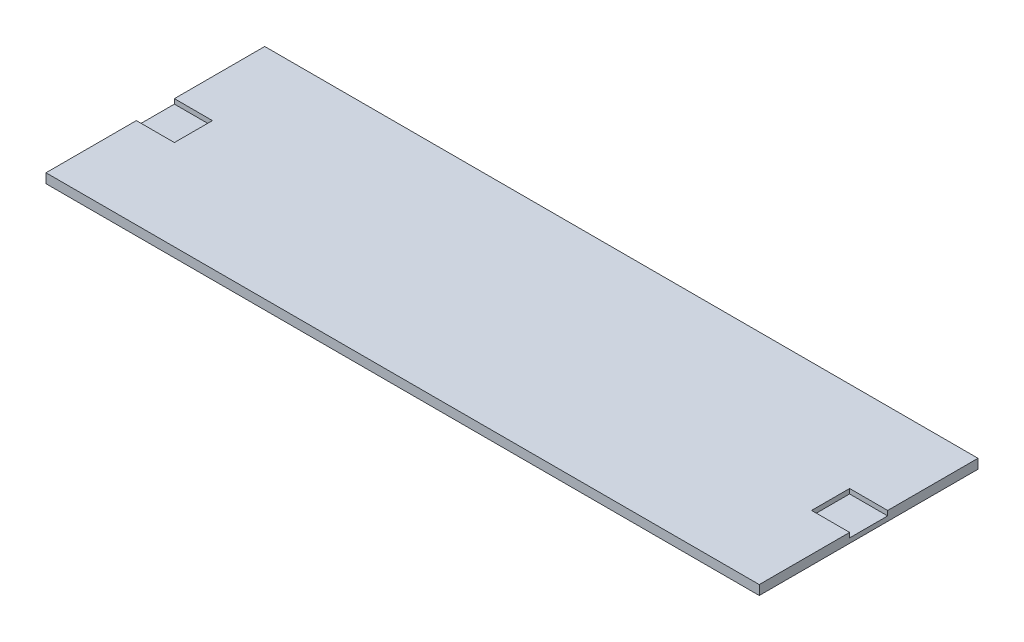
SolidWorks part; units mm, degrees
material "A-Glass Fiber"
ref_plane "Front Plane" through (0, 0, 0) normal (0, 0, 1) x (1, 0, 0)
ref_plane "Top Plane" through (0, 0, 0) normal (0, 1, 0) x (1, 0, 0)
ref_plane "Right Plane" through (0, 0, 0) normal (1, 0, 0) x (0, 0, -1)
sketch "Sketch1" plane through (0, 0, 0) normal (0, 1, 0) x (1, 0, 0)
  line L1 (-89.1211, 55.7339) -> (387.1289, 55.7339)
  line L2 (-89.1211, 55.7339) -> (-89.1211, -90.3161)
  line L3 (-89.1211, -90.3161) -> (387.1289, -90.3161)
  line L4 (387.1289, 55.7339) -> (387.1289, -90.3161)
  dimension "D1" = 476.25
  dimension "D2" = 146.05
extrude "Boss-Extrude1" add sketch "Sketch1" along normal blind 6.35
sketch "Sketch2" plane through (0, 6.35, 0) normal (0, 1, 0) x (1, 0, 0)
  line L0 (-89.1211, 55.7339) -> (-89.1211, -90.3161) construction
  line L1 (-89.1211, -4.5911) -> (-63.7211, -4.5911)
  line L2 (-89.1211, -4.5911) -> (-89.1211, -29.9911)
  line L3 (-89.1211, -29.9911) -> (-63.7211, -29.9911)
  line L4 (-63.7211, -4.5911) -> (-63.7211, -29.9911)
  line L5 (387.1289, -90.3161) -> (387.1289, 55.7339) construction
  line L6 (387.1289, -4.5911) -> (361.7289, -4.5911)
  line L7 (387.1289, -4.5911) -> (387.1289, -29.9911)
  line L8 (387.1289, -29.9911) -> (361.7289, -29.9911)
  line L9 (361.7289, -4.5911) -> (361.7289, -29.9911)
  line L10 (387.1289, 55.7339) -> (-89.1211, 55.7339) construction
  line L11 (-89.1211, -90.3161) -> (387.1289, -90.3161) construction
  dimension "D1" = 25.4
  dimension "D2" = 25.4
  dimension "D3" = 25.4
  dimension "D4" = 25.4
  dimension "D5" = 60.325
  dimension "D6" = 60.325
  dimension "D7" = 60.325
  dimension "D8" = 60.325
extrude "Cut-Extrude1" cut sketch "Sketch2" against normal blind 3.175
